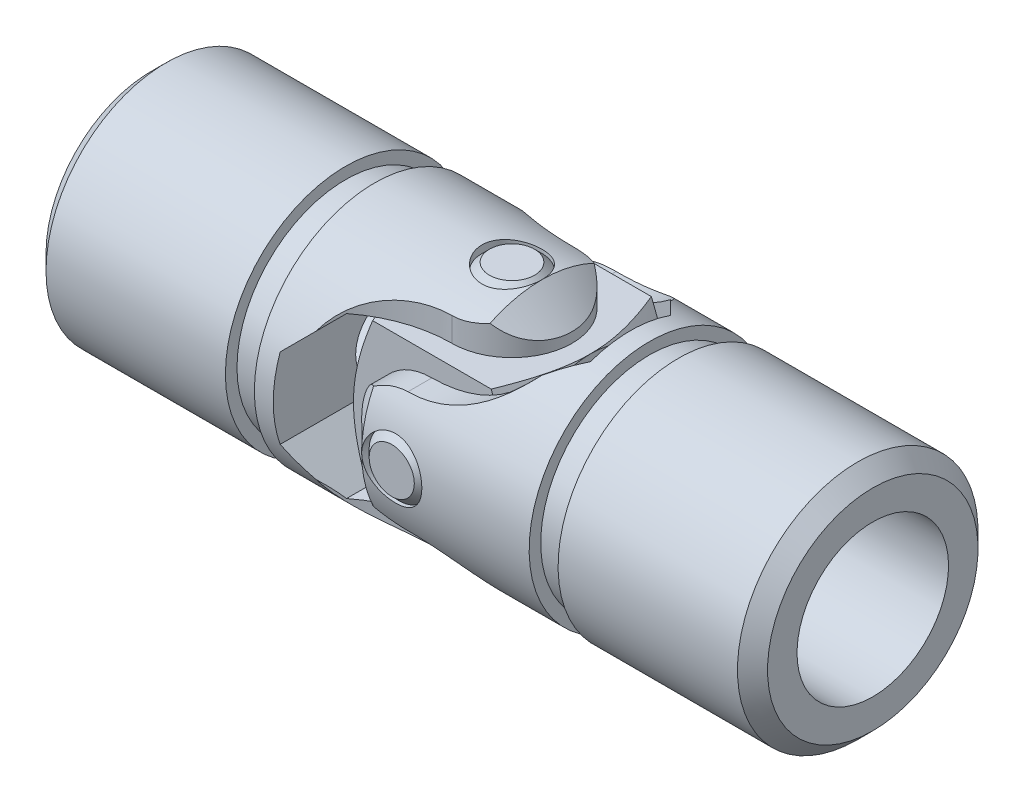
SolidWorks part; units mm, degrees
ref_plane "Front Plane" through (0, 0, 0) normal (0, 0, 1) x (1, 0, 0)
ref_plane "Top Plane" through (0, 0, 0) normal (0, 1, 0) x (1, 0, 0)
ref_plane "Right Plane" through (0, 0, 0) normal (1, 0, 0) x (0, 0, -1)
sketch "Sketch0" plane through (0, 0, 0) normal (0, 1, 0) x (1, 0, 0)
  line L0 (-47.625, 0) -> (47.625, 0) construction
  line L1 (-47.625, 15.875) -> (-47.625, -15.875) construction
  line L2 (-20.6375, 10) -> (-20.6375, -10) construction
  line L3 (-20.6375, 10) -> (-10.6375, 0) construction
  line L4 (-10.6375, 0) -> (-20.6375, -10) construction
  line L5 (-15.6375, 5) -> (-15.6375, -5) construction
  point P7 (-20.6375, 0)
  point P8 (0, 0)
  point P12 (-15.6375, 0)
sketch "Sketch1" plane through (0, 0, 0) normal (0, 1, 0) x (1, 0, 0)
  line L0 (-47.625, 15.875) -> (-21.9574, 15.875)
  line L1 (7.9375, 15.875) -> (7.9375, 0)
  line L2 (7.9375, 0) -> (-47.625, 0)
  line L3 (-47.625, 0) -> (-47.625, 15.875)
  line L4 (-47.625, 15.875) -> (-47.625, -15.875) construction
  line L5 (-47.625, 0) -> (47.625, 0) construction
  line L6 (-18.1375, 15.875) -> (7.9375, 15.875)
  line L7 (-18.1375, 5) -> (-18.1375, 14.347) construction
  line L8 (-21.9574, 15.875) -> (-21.9574, 14.347)
  line L9 (-21.9574, 14.347) -> (-18.1375, 14.347)
  line L10 (-18.1375, 15.875) -> (-18.1375, 14.347)
  line L11 (0, 0) -> (15.875, 0) construction
  line L12 (-15.6375, 5) -> (-20.6375, 5) construction
  line L13 (-20.6375, 10) -> (-20.6375, -10) construction
  circle A0 centre (0, 0) radius 15.875 construction
  dimension "D1" = 3.8199
  dimension "D2" = 1.528
  dimension "D3" = 55.5625
revolve "Revolve1" add sketch "Sketch1" angle 360 about L0
chamfer "Chamfer1" distance 1.9844 angle 45 1 edges at (-47.625, 0, 15.875)
chamfer "Chamfer2" distance 3.9688 angle 45 1 edges at (7.9375, 0, 15.875)
sketch "Sketch2" plane through (0, 0, 0) normal (0, 1, 0) x (1, 0, 0)
  line L0 (-18.1375, 15.875) -> (-14.3176, 15.875) construction
  line L1 (-18.1375, 15.875) -> (7.9375, 15.875) construction
  line L2 (3.9687, 15.875) -> (-18.1375, 15.875) construction
  line L3 (-21.9574, 14.347) -> (-18.1375, 14.347) construction
  line L4 (-47.625, 0) -> (7.9375, 0) construction
  line L5 (-14.3176, 15.875) -> (15.875, 15.875)
  line L6 (15.875, 15.875) -> (15.875, -15.875)
  line L7 (15.875, -15.875) -> (-14.3176, -15.875)
  line L8 (0, 7.9375) -> (0, 0) construction
  arc A0 (-14.3176, 15.875) -> (0, 7.9375) centre (0, 24.8192) ccw
  arc A1 (0, -7.9375) -> (0, 7.9375) centre (0, 0) ccw
  arc A2 (-14.3176, -15.875) -> (0, -7.9375) centre (0, -24.8192) cw
  dimension "D1" = 15.875
extrude "Extrude1" cut sketch "Sketch2" against normal through all and the other way through all
sketch "Sketch3" plane through (0, 0, 0) normal (0, 0, 1) x (1, 0, 0)
  line L0 (-10.3511, 10.5728) -> (-15.6375, 5.2864)
  line L1 (-10.3511, 10.5728) -> (15.875, 10.5728)
  line L2 (-15.6375, 5.2864) -> (-15.6375, -5.2864)
  line L3 (-10.3511, -10.5728) -> (15.875, -10.5728)
  line L4 (15.875, 10.5728) -> (15.875, -10.5728)
  line L5 (-15.6375, -5.2864) -> (-10.3511, -10.5728)
  dimension "D1" = 21.1455
  dimension "D2" = 5.2864
extrude "Extrude3" cut sketch "Sketch3" against normal through all and the other way through all
sketch "Sketch4" plane through (-47.625, 0, 0) normal (-1, 0, 0) x (0, 0, 1)
  circle A0 centre (0, 0) radius 10
extrude "Extrude4" cut sketch "Sketch4" against normal up to vertex (26.9875 mm away) up to point (-20.6375, 0, -10)
sketch "Sketch5" plane through (-20.6375, 0, 0) normal (-1, 0, 0) x (0, 0, 1)
  circle A0 centre (0, 0) radius 10 construction
  circle A1 centre (0, 0) radius 10
extrude "Extrude5" cut sketch "Sketch5" against normal through all draft 45
sketch "Sketch6" plane through (0, 0, 0) normal (0, 1, 0) x (1, 0, 0)
  line L0 (-47.625, 0) -> (47.625, 0) construction
  line L1 (7.9375, 0) -> (3.9687, 0) construction
  line L2 (3.9687, 0) -> (0, 0) construction
  circle A0 centre (0, 0) radius 3.9687
  arc A1 (0, -7.9375) -> (0, 7.9375) centre (0, 0) ccw construction
  dimension "D1" = 7.9375
extrude "Extrude6" cut sketch "Sketch6" against normal through all and the other way through all
mirror "Mirror1" about plane through (0, 0, 0) normal (1, 0, 0) of bodies 109 122
move or copy body "Body-Move/Copy1" bodies to move or copy 110 copy no rotation origin (0, 0, 0) rotation axis (1, 0, 0) rotation angle 90
sketch "Sketch18" plane through (0, 0, 0) normal (0, 1, 0) x (1, 0, 0)
  line L0 (-47.625, -10) -> (-20.6375, -10)
  line L3 (-47.625, 10) -> (-20.6375, 10)
  line L4 (-20.6375, 10) -> (-20.6375, -10)
  line L5 (20.6375, 10) -> (20.6375, -10)
  line L6 (20.6375, -10) -> (47.625, -10)
  line L7 (20.6375, 10) -> (47.625, 10)
  line L8 (0, 0) -> (20.6375, 0) construction
  line L9 (47.625, -13.8906) -> (47.625, 13.8906) construction
  line L11 (-20.6375, -10) -> (-20.6375, 10) construction
sketch "Sketch10" plane through (0, 0, 0) normal (0, 0, 1) x (1, 0, 0)
  line L0 (-10.3511, 10.5728) -> (10.3511, -10.5727) construction
  line L1 (-10.3511, 10.5728) -> (10.3511, 10.5728)
  line L2 (-10.3511, 10.5728) -> (-10.3511, -10.5727)
  line L3 (-10.3511, -10.5727) -> (10.3511, -10.5727)
  line L4 (10.3511, 10.5728) -> (10.3511, -10.5727)
  line L5 (0, 10.5728) -> (7.9375, 10.5728) construction
extrude "Extrude10" add sketch "Sketch10" against normal up to surface and the other way up to surface separate body up to face at (-3.9687, 0, -10.5728) other way up to face at (3.9688, 0, 10.5728)
sketch "Sketch11" plane through (10.3511, 0, 0) normal (1, 0, 0) x (0, 0, -1)
  line L4 (-10.5728, -10.5728) -> (-10.5728, 10.5728) construction
  circle A0 centre (0, 0) radius 10.5728
extrude "Extrude11" cut sketch "Sketch11" against normal through all draft 60 flip side to cut
sketch "Sketch12" plane through (-10.3511, -21.0185, 0) normal (1, 0, 0) x (0, -1, 0)
  circle A2 centre (-21.0185, 0) radius 10.5728
  circle A6 centre (-21.0185, 0) radius 10.5728
  dimension "D1" = 0
extrude "Extrude12" cut sketch "Sketch12" along normal through all draft 60 flip side to cut
sketch "Sketch13" plane through (0, 0, 0) normal (0, 1, 0) x (1, 0, 0)
  circle A0 centre (0, 0) radius 3.9687 construction
  circle A1 centre (0, 0) radius 3.9687
extrude "Extrude13" cut sketch "Sketch13" against normal through all and the other way through all
sketch "Sketch14" plane through (0, 0, 0) normal (0, 1, 0) x (1, 0, 0)
  circle A1 centre (0, 0) radius 3.9687
  circle A2 centre (0, 0) radius 3.9687
  dimension "D1" = 0
extrude "Extrude14" add sketch "Sketch14" along normal mid plane 31.75 separate body
sketch "Sketch15" plane through (0, 0, 0) normal (0, 0, 1) x (1, 0, 0)
  circle A0 centre (0, 0) radius 3.9687 construction
  circle A1 centre (0, 0) radius 3.9688
extrude "Extrude15" cut sketch "Sketch15" against normal through all and the other way through all
sketch "Sketch16" plane through (0, 0, 0) normal (0, 0, 1) x (1, 0, 0)
  circle A1 centre (0, 0) radius 3.9688
  circle A2 centre (0, 0) radius 3.9688
  dimension "D1" = 0
extrude "Extrude16" add sketch "Sketch16" along normal mid plane 31.75
chamfer "Chamfer3" distance 0.9922 angle 45 4 edges at (0, -15.875, 3.9687) (0, 15.875, 3.9687) (3.9688, 0, 15.875) (3.9688, 0, -15.875)
move or copy body "Body-Move/Copy2" [suppressed] bodies to move or copy 124 111 copy no rotation origin (0, 0, 0) rotation axis (0, 0, -1) rotation angle 25
equation "\"D2@Sketch3\" = \"D1@Sketch3\" / 4"
equation "\"D1@Extrude14\" = \"OD@Sketch0\""
equation "\"D1@Extrude16\" = \"D1@Extrude14\""
equation "\"D1@Sketch3\" = \"OD@Sketch0\"*.666"
equation "\"D2@Sketch3\" = \"D1@Sketch3\"/4"
equation "\"D1@Sketch1\" = \"D3@Sketch1\"*.06875"
equation "\"D2@Sketch1\" = \"D1@Sketch1\"/2.5"
equation "\"D1@Chamfer1\" = \"OD@Sketch0\"/16"
equation "\"D1@Chamfer2\" = \"D1@Chamfer1\"*2"
equation "\"D1@Chamfer3\" = \"D1@Chamfer1\"*.50"
